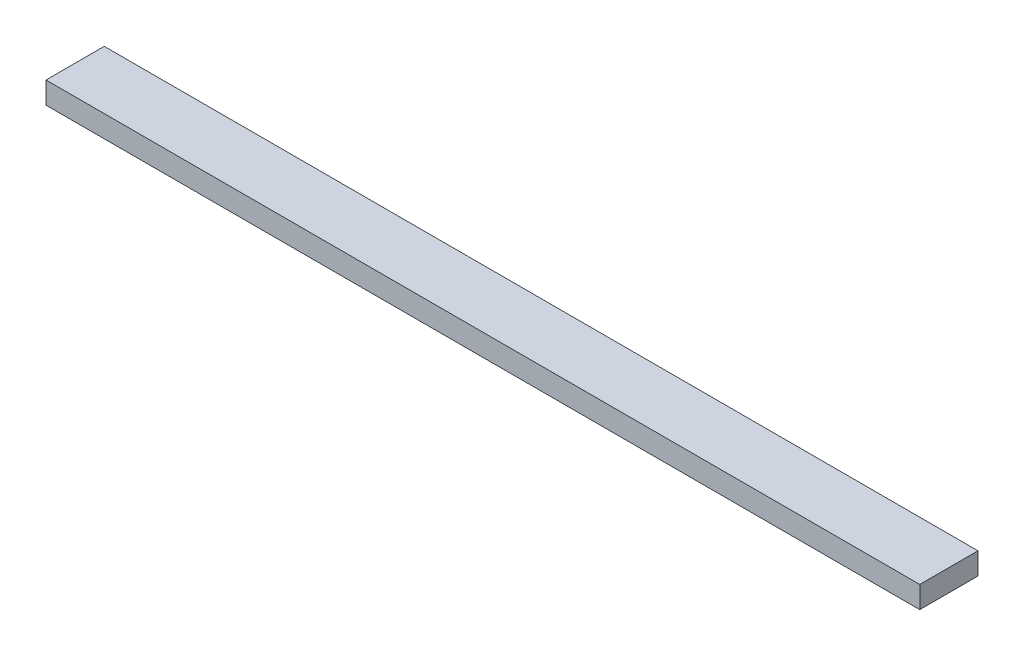
SolidWorks part; units mm, degrees
ref_plane "Front Plane" through (0, 0, 0) normal (0, 0, 1) x (1, 0, 0)
ref_plane "Top Plane" through (0, 0, 0) normal (0, 1, 0) x (1, 0, 0)
ref_plane "Right Plane" through (0, 0, 0) normal (1, 0, 0) x (0, 0, -1)
sketch "Sketch1" plane through (0, 0, 0) normal (0, 1, 0) x (1, 0, 0)
  line L1 (-381, -25.4) -> (381, -25.4)
  line L2 (-381, -25.4) -> (-381, 25.4)
  line L3 (-381, 25.4) -> (381, 25.4)
  line L4 (381, -25.4) -> (381, 25.4)
  line L5 (-381, -25.4) -> (381, 25.4) construction
  line L6 (-381, 25.4) -> (381, -25.4) construction
  point P0 (0, 0)
  dimension "D1" = 50.8
  dimension "D2" = 762
extrude "Boss-Extrude1" add sketch "Sketch1" along normal blind 19.05
